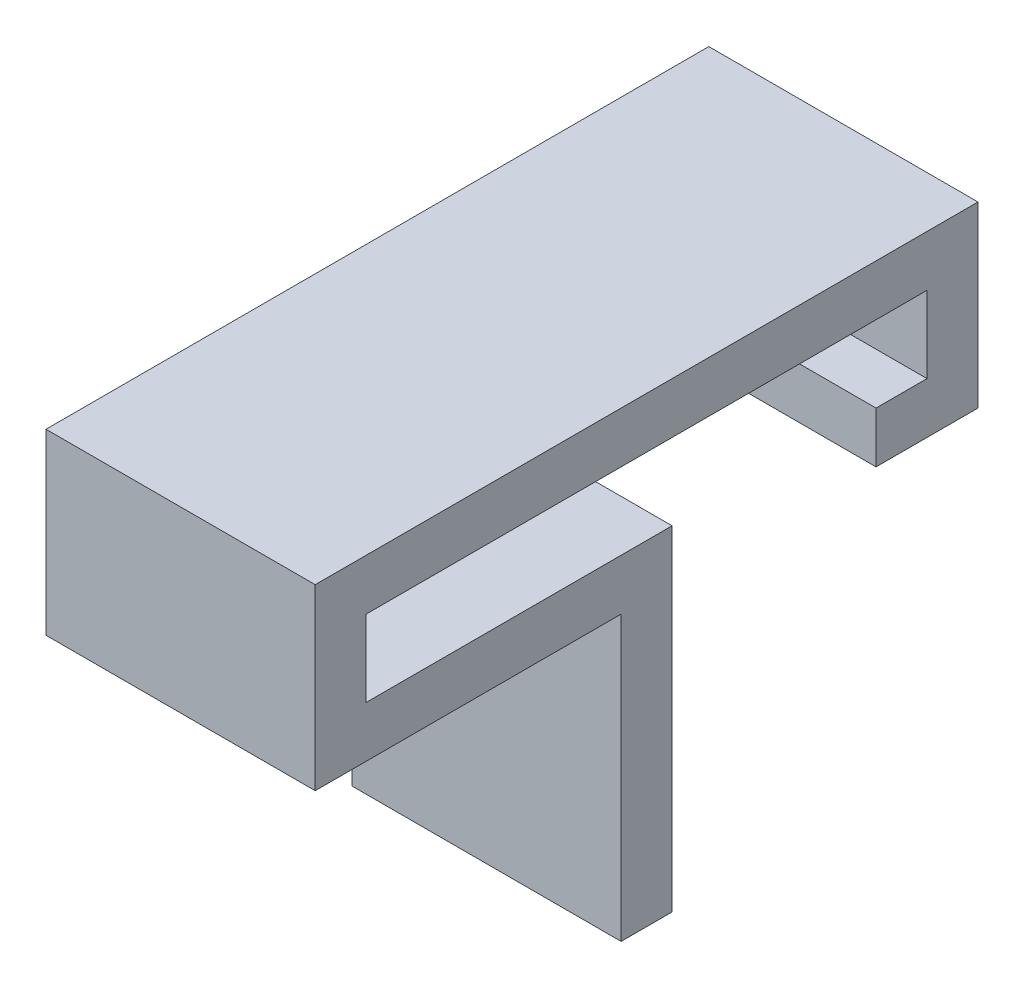
SolidWorks part; units mm, degrees
ref_plane "Front Plane" through (0, 0, 0) normal (0, 0, 1) x (1, 0, 0)
ref_plane "Top Plane" through (0, 0, 0) normal (0, 1, 0) x (1, 0, 0)
ref_plane "Right Plane" through (0, 0, 0) normal (1, 0, 0) x (0, 0, -1)
sketch "Sketch1" plane through (0, 0, 0) normal (0, 0, 1) x (1, 0, 0)
  line L1 (-16.2929, 14.3046) -> (10.1071, 14.3046)
  line L2 (-16.2929, 14.3046) -> (-16.2929, -18.4954)
  line L3 (-16.2929, -18.4954) -> (10.1071, -18.4954)
  line L4 (10.1071, 14.3046) -> (10.1071, -18.4954)
  dimension "D1" = 26.4
  dimension "D2" = 32.8
extrude "Boss-Extrude1" add sketch "Sketch1" along normal blind 5
sketch "Sketch2" plane through (0, 0, 5) normal (0, 0, 1) x (1, 0, 0)
  line L0 (10.1071, -18.4954) -> (10.1071, 14.3046) construction
  line L1 (-16.2929, 14.3046) -> (10.1071, 14.3046)
  line L2 (-16.2929, 14.3046) -> (-16.2929, 9.3046)
  line L3 (-16.2929, 9.3046) -> (10.1071, 9.3046)
  line L4 (10.1071, 14.3046) -> (10.1071, 9.3046)
  dimension "D1" = 5
extrude "Boss-Extrude2" add sketch "Sketch2" along normal blind 30
sketch "Sketch3" plane through (0, 14.3046, 0) normal (0, 1, 0) x (1, 0, 0)
  line L0 (10.1071, -35) -> (10.1071, 0) construction
  line L1 (-16.2929, -35) -> (10.1071, -35)
  line L2 (-16.2929, -35) -> (-16.2929, -30)
  line L3 (-16.2929, -30) -> (10.1071, -30)
  line L4 (10.1071, -35) -> (10.1071, -30)
  dimension "D1" = 5
extrude "Boss-Extrude3" add sketch "Sketch3" along normal blind 12.5
sketch "Sketch4" plane through (0, 0, 30) normal (0, 0, -1) x (-1, 0, 0)
  line L0 (-10.1071, 26.8046) -> (-10.1071, 14.3046) construction
  line L1 (16.2929, 26.8046) -> (-10.1071, 26.8046)
  line L2 (16.2929, 26.8046) -> (16.2929, 21.8046)
  line L3 (16.2929, 21.8046) -> (-10.1071, 21.8046)
  line L4 (-10.1071, 26.8046) -> (-10.1071, 21.8046)
  dimension "D1" = 5
extrude "Boss-Extrude4" add sketch "Sketch4" along normal blind 60
sketch "Sketch5" plane through (0, 21.8046, 0) normal (0, -1, 0) x (1, 0, 0)
  line L0 (-16.2929, -30) -> (-16.2929, 30) construction
  line L1 (10.1071, -30) -> (-16.2929, -30)
  line L2 (10.1071, -30) -> (10.1071, -25)
  line L3 (10.1071, -25) -> (-16.2929, -25)
  line L4 (-16.2929, -30) -> (-16.2929, -25)
  dimension "D1" = 5
extrude "Boss-Extrude5" add sketch "Sketch5" along normal blind 12.5
sketch "Sketch6" plane through (0, 0, -25) normal (0, 0, 1) x (1, 0, 0)
  line L0 (-16.2929, 9.3046) -> (-16.2929, 21.8046) construction
  line L1 (10.1071, 9.3046) -> (-16.2929, 9.3046)
  line L2 (10.1071, 9.3046) -> (10.1071, 14.3046)
  line L3 (10.1071, 14.3046) -> (-16.2929, 14.3046)
  line L4 (-16.2929, 9.3046) -> (-16.2929, 14.3046)
  dimension "D1" = 5
extrude "Boss-Extrude8" add sketch "Sketch6" along normal blind 5
